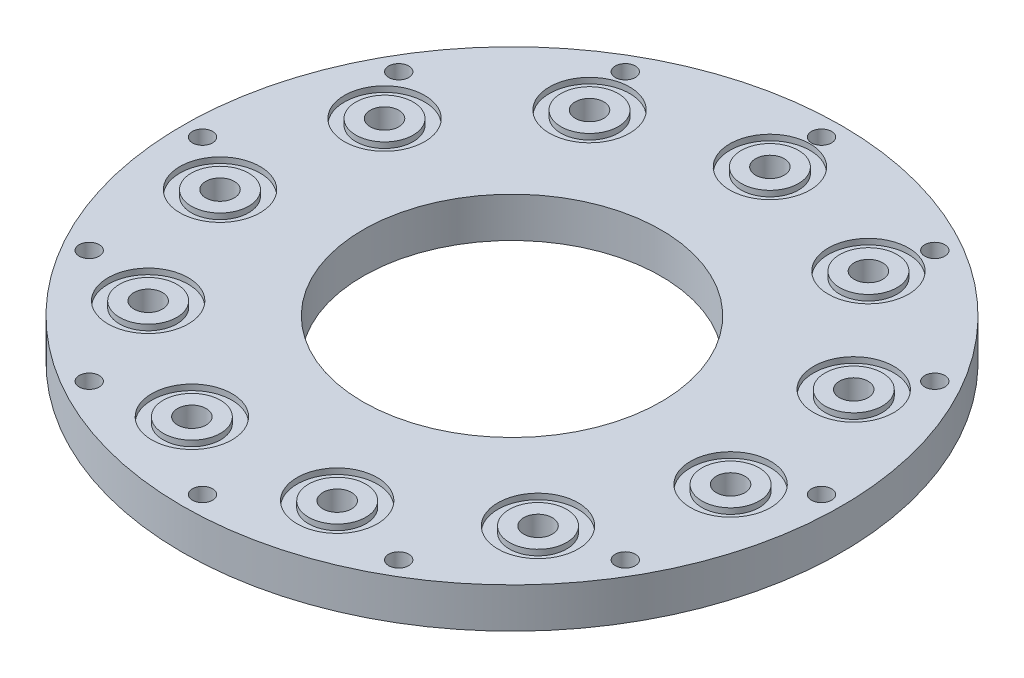
SolidWorks part; units mm, degrees
ref_plane "Front Plane" through (0, 0, 0) normal (0, 0, 1) x (1, 0, 0)
ref_plane "Top Plane" through (0, 0, 0) normal (0, 1, 0) x (1, 0, 0)
ref_plane "Right Plane" through (0, 0, 0) normal (1, 0, 0) x (0, 0, -1)
sketch "Sketch1" plane through (0, 0, 0) normal (0, 1, 0) x (1, 0, 0)
  circle A0 centre (0, 0) radius 57.5
  circle A1 centre (0, 0) radius 54 construction
  circle A2 centre (0, 54) radius 1.75
  circle A3 centre (27, 46.7654) radius 1.75
  circle A4 centre (46.7654, 27) radius 1.75
  circle A5 centre (54, 0) radius 1.75
  circle A6 centre (46.7654, -27) radius 1.75
  circle A7 centre (27, -46.7654) radius 1.75
  circle A8 centre (0, -54) radius 1.75
  circle A9 centre (-27, -46.7654) radius 1.75
  circle A10 centre (-46.7654, -27) radius 1.75
  circle A11 centre (-54, 0) radius 1.75
  circle A12 centre (-46.7654, 27) radius 1.75
  circle A13 centre (-27, 46.7654) radius 1.75
  circle A14 centre (0, 0) radius 26
  circle A15 centre (0, 0) radius 45 construction
  circle A16 centre (0, 45) radius 2.5
  circle A17 centre (24.3288, 37.8564) radius 2.5
  circle A18 centre (40.9334, 18.6937) radius 2.5
  circle A19 centre (44.542, -6.4042) radius 2.5
  circle A20 centre (34.0087, -29.4687) radius 2.5
  circle A21 centre (12.678, -43.1772) radius 2.5
  circle A22 centre (-12.678, -43.1772) radius 2.5
  circle A23 centre (-34.0087, -29.4687) radius 2.5
  circle A24 centre (-44.542, -6.4042) radius 2.5
  circle A25 centre (-40.9334, 18.6937) radius 2.5
  circle A26 centre (-24.3288, 37.8564) radius 2.5
  point P31 (0, 0)
  point P55 (0, 0)
  dimension "D1" = 115
  dimension "D2" = 108
  dimension "D3" = 3.5
  dimension "D4" = 52
  dimension "D5" = 90
  dimension "D6" = 5
extrude "Boss-Extrude1" add sketch "Sketch1" along normal blind 7
sketch "Sketch2" plane through (0, 7, 0) normal (0, 1, 0) x (1, 0, 0)
  circle A0 centre (0, 0) radius 45 construction
  circle A1 centre (0, 45) radius 7
  circle A2 centre (24.3288, 37.8564) radius 7
  circle A3 centre (40.9334, 18.6937) radius 7
  circle A4 centre (44.542, -6.4042) radius 7
  circle A5 centre (34.0087, -29.4687) radius 7
  circle A6 centre (12.678, -43.1772) radius 7
  circle A7 centre (-12.678, -43.1772) radius 7
  circle A8 centre (-34.0087, -29.4687) radius 7
  circle A9 centre (-44.542, -6.4042) radius 7
  circle A10 centre (-40.9334, 18.6937) radius 7
  circle A11 centre (-24.3288, 37.8564) radius 7
  circle A12 centre (0, 45) radius 5
  circle A13 centre (24.3288, 37.8564) radius 5
  circle A14 centre (40.9334, 18.6937) radius 5
  circle A15 centre (44.542, -6.4042) radius 5
  circle A16 centre (34.0087, -29.4687) radius 5
  circle A17 centre (12.678, -43.1772) radius 5
  circle A18 centre (-12.678, -43.1772) radius 5
  circle A19 centre (-34.0087, -29.4687) radius 5
  circle A20 centre (-44.542, -6.4042) radius 5
  circle A21 centre (-40.9334, 18.6937) radius 5
  circle A22 centre (-24.3288, 37.8564) radius 5
  point P28 (0, 0)
  point P51 (0, 0)
  dimension "D1" = 14
  dimension "D3" = 10
  dimension "D2" = 11
  dimension "D4" = 11
extrude "Cut-Extrude1" cut sketch "Sketch2" against normal blind 1
